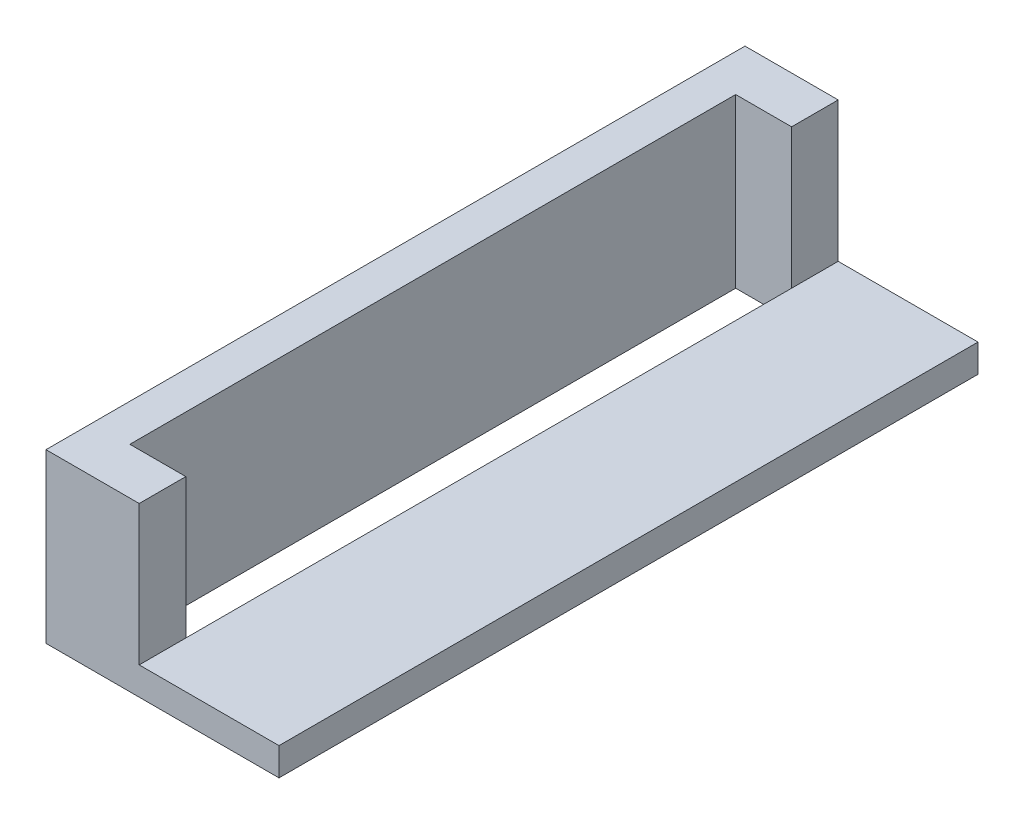
SolidWorks part; units mm, degrees
ref_plane "Plano frontal" through (0, 0, 0) normal (0, 0, 1) x (1, 0, 0)
ref_plane "Plano superior" through (0, 0, 0) normal (0, 1, 0) x (1, 0, 0)
ref_plane "Plano direito" through (0, 0, 0) normal (1, 0, 0) x (0, 0, -1)
sketch "Esboço1" plane through (0, 0, 0) normal (0, 1, 0) x (1, 0, 0)
  line L1 (0, 0) -> (-5, 0)
  line L2 (0, 0) -> (0, 15)
  line L3 (0, 15) -> (-5, 15)
  line L4 (-5, 0) -> (-5, 15)
  dimension "D1" = 5
  dimension "D2" = 15
extrude "Ressalto-extrusão1" add sketch "Esboço1" along normal blind 3.6
sketch "Esboço2" plane through (0, 3.6, 0) normal (0, 1, 0) x (1, 0, 0)
  line L1 (0, 15) -> (-3, 15)
  line L2 (0, 15) -> (0, 0)
  line L3 (0, 0) -> (-3, 0)
  line L4 (-3, 15) -> (-3, 0)
  line L5 (-5, 0) -> (0, 0) construction
  point P5 (-3, 0)
  dimension "D1" = 3
extrude "Corte-extrusão2" cut sketch "Esboço2" against normal blind 3
sketch "Esboço3" plane through (0, 3.6, 0) normal (0, 1, 0) x (1, 0, 0)
  line L0 (-3, 15) -> (-3, 0) construction
  line L1 (-3, 14) -> (-4.2, 14)
  line L2 (-3, 14) -> (-3, 1)
  line L3 (-3, 1) -> (-4.2, 1)
  line L4 (-4.2, 14) -> (-4.2, 1)
  line L5 (-3, 15) -> (-5, 15) construction
  dimension "D1" = 1.2
  dimension "D2" = 13
  dimension "D3" = 1
extrude "Corte-extrusão3" cut sketch "Esboço3" against normal through all
